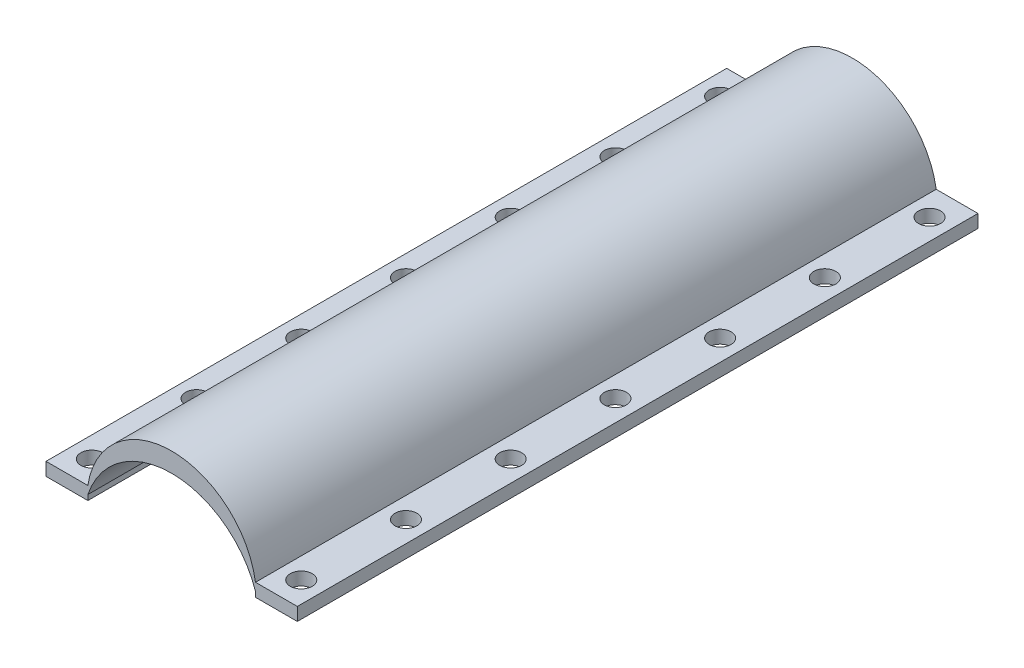
SolidWorks part; units mm, degrees
ref_plane "Front Plane" through (0, 0, 0) normal (0, 0, 1) x (1, 0, 0)
ref_plane "Top Plane" through (0, 0, 0) normal (0, 1, 0) x (1, 0, 0)
ref_plane "Right Plane" through (0, 0, 0) normal (1, 0, 0) x (0, 0, -1)
sketch "Sketch1" plane through (0, 0, 0) normal (0, 0, 1) x (1, 0, 0)
  line L3 (0, 0) -> (50.8, 0) construction
  line L7 (-5.08, 0) -> (5.08, 0)
  line L8 (45.72, 0) -> (55.88, 0)
  line L9 (-5.08, 0) -> (-5.08, 3.1617)
  line L10 (-5.08, 3.1617) -> (5.0637, 3.1617)
  line L11 (55.88, 0) -> (55.88, 3.1617)
  line L12 (55.88, 3.1617) -> (45.7363, 3.1617)
  line L13 (5.08, 0) -> (5.08, 1.27)
  line L14 (45.72, 0) -> (45.72, 1.27)
  arc A2 (5.0637, 3.1617) -> (45.7363, 3.1617) centre (25.4, 0) cw
  arc A3 (5.08, 1.27) -> (45.72, 1.27) centre (25.4, -5.5332) cw
  point P6 (0, 0)
  point P9 (50.8, 0)
  dimension "D1" = 50.8
  dimension "D4" = 1.27
  dimension "D2" = 10.16
  dimension "D3" = 10.16
extrude "Boss-Extrude1" add sketch "Sketch1" along normal blind 165.1
sketch "Sketch3" plane through (0, 3.1617, 0) normal (0, 1, 0) x (1, 0, 0)
  line L0 (0, 0) -> (0, -6.6675) construction
  line L2 (-5.08, -6.6675) -> (0, -6.6675) construction
  line L3 (-5.08, -165.1) -> (-5.08, 0) construction
  line L4 (-5.08, 0) -> (25.4, 0) construction
  line L5 (45.7363, 0) -> (5.0637, 0) construction
  line L6 (25.4, 0) -> (25.4, -165.1) construction
  line L7 (5.0637, -165.1) -> (45.7363, -165.1) construction
  circle A0 centre (0, -6.6675) radius 2.667
  circle A1 centre (0, -32.0675) radius 2.667
  circle A2 centre (0, -57.4675) radius 2.667
  circle A3 centre (0, -82.8675) radius 2.667
  circle A4 centre (0, -108.2675) radius 2.667
  circle A5 centre (0, -133.6675) radius 2.667
  circle A6 centre (0, -159.0675) radius 2.667
  circle A7 centre (50.8, -159.0675) radius 2.667
  circle A8 centre (50.8, -133.6675) radius 2.667
  circle A9 centre (50.8, -108.2675) radius 2.667
  circle A10 centre (50.8, -82.8675) radius 2.667
  circle A11 centre (50.8, -57.4675) radius 2.667
  circle A12 centre (50.8, -32.0675) radius 2.667
  circle A13 centre (50.8, -6.6675) radius 2.667
  dimension "D1" = 5.334
  dimension "D3" = 6.6675
  dimension "D2" = 7
extrude "Cut-Extrude1" cut sketch "Sketch3" against normal blind 165.1
